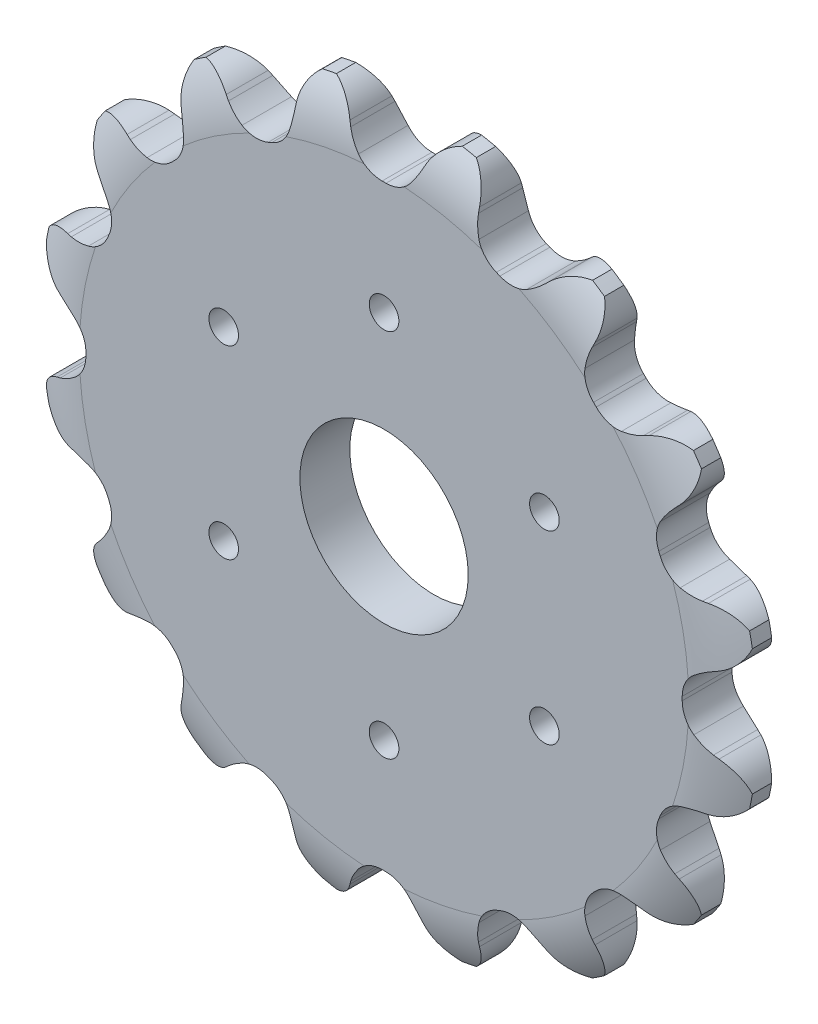
SolidWorks part; units mm, degrees
material "AISI 304"
ref_plane "Спереди" through (0, 0, 0) normal (0, 0, 1) x (1, 0, 0)
ref_plane "Сверху" through (0, 0, 0) normal (0, 1, 0) x (1, 0, 0)
ref_plane "Справа" through (0, 0, 0) normal (1, 0, 0) x (0, 0, -1)
other "Configuration Table"
sketch "Эскиз1" plane through (0, 0, 0) normal (0, 0, 1) x (1, 0, 0)
  line L0 (0, 0) -> (0, 106.534) construction
  line L1 (-0.572, 88.5752) -> (-0.572, 97.6453) construction
  line L2 (0, 0) -> (-23.7583, 119.4411) construction
  line L3 (-0.572, 97.6453) -> (-7.6457, 91.9681) construction
  line L4 (-0.572, 97.6453) -> (10.627, 106.6335) construction
  line L5 (-10.7356, 97.0103) -> (10.627, 106.6335) construction
  line L6 (-10.7356, 97.0103) -> (-11.3155, 98.2977)
  line L7 (-11.3155, 98.2977) -> (-22.4025, 93.3034) construction
  line L8 (10.7356, 97.0103) -> (11.3155, 98.2977)
  line L9 (27.2059, 93.7342) -> (27.1627, 95.1455)
  line L10 (47.0426, 85.5175) -> (48.0711, 86.485)
  line L11 (61.0055, 76.1879) -> (61.5057, 77.5083)
  line L12 (76.1879, 61.0055) -> (77.5083, 61.5057)
  line L13 (85.5175, 47.0426) -> (86.485, 48.0711)
  line L14 (93.7342, 27.2059) -> (95.1455, 27.1627)
  line L15 (97.0103, 10.7356) -> (98.2977, 11.3155)
  line L16 (97.0103, -10.7356) -> (98.2977, -11.3155)
  line L17 (93.7342, -27.2059) -> (95.1455, -27.1627)
  line L18 (85.5175, -47.0426) -> (86.485, -48.0711)
  line L19 (76.1879, -61.0055) -> (77.5083, -61.5057)
  line L20 (61.0055, -76.1879) -> (61.5057, -77.5083)
  line L21 (47.0426, -85.5175) -> (48.0711, -86.485)
  line L22 (27.2059, -93.7342) -> (27.1627, -95.1455)
  line L23 (10.7356, -97.0103) -> (11.3155, -98.2977)
  line L24 (-10.7356, -97.0103) -> (-11.3155, -98.2977)
  line L25 (-27.2059, -93.7342) -> (-27.1627, -95.1455)
  line L26 (-47.0426, -85.5175) -> (-48.0711, -86.485)
  line L27 (-61.0055, -76.1879) -> (-61.5057, -77.5083)
  line L28 (-76.1879, -61.0055) -> (-77.5083, -61.5057)
  line L29 (-85.5175, -47.0426) -> (-86.485, -48.0711)
  line L30 (-93.7342, -27.2059) -> (-95.1455, -27.1627)
  line L31 (-97.0103, -10.7356) -> (-98.2977, -11.3155)
  line L32 (-97.0103, 10.7356) -> (-98.2977, 11.3155)
  line L33 (-93.7342, 27.2059) -> (-95.1455, 27.1627)
  line L34 (-85.5175, 47.0426) -> (-86.485, 48.0711)
  line L35 (-76.1879, 61.0055) -> (-77.5083, 61.5057)
  line L36 (-61.0055, 76.1879) -> (-61.5057, 77.5083)
  line L37 (-47.0426, 85.5175) -> (-48.0711, 86.485)
  line L38 (-27.2059, 93.7342) -> (-27.1627, 95.1455)
  arc A0 (-18.6878, 104.8821) -> (-22.8713, 104.05) centre (0, 0) ccw
  circle A1 centre (0, 0) radius 97.647 construction
  arc A2 (0.572, 88.5752) -> (-0.572, 88.5752) centre (0, 0) ccw
  arc A3 (-0.572, 88.5752) -> (-7.6457, 91.9681) centre (-0.572, 97.6453) cw
  arc A4 (-7.6457, 91.9681) -> (-10.7356, 97.0103) centre (10.627, 106.6335) cw
  arc A5 (-11.3155, 98.2977) -> (-18.6878, 104.8821) centre (-22.4025, 93.3034) ccw
  arc A6 (0.572, 88.5752) -> (7.6457, 91.9681) centre (0.572, 97.6453) ccw
  arc A7 (7.6457, 91.9681) -> (10.7356, 97.0103) centre (-10.627, 106.6335) ccw
  arc A8 (11.3155, 98.2977) -> (18.6878, 104.8821) centre (22.4025, 93.3034) cw
  arc A9 (27.1627, 95.1455) -> (22.8713, 104.05) centre (15.0084, 94.7742) ccw
  arc A10 (28.131, 87.8933) -> (27.2059, 93.7342) centre (50.6249, 94.4497) cw
  arc A11 (33.3678, 82.0517) -> (28.131, 87.8933) centre (36.8388, 90.4314) cw
  arc A12 (34.4247, 81.6139) -> (33.3678, 82.0517) centre (0, 0) ccw
  arc A13 (34.4247, 81.6139) -> (42.2584, 82.0416) centre (37.8957, 89.9936) ccw
  arc A14 (42.2584, 82.0416) -> (47.0426, 85.5175) centre (30.9888, 102.5833) ccw
  arc A15 (48.0711, 86.485) -> (57.402, 89.7469) centre (56.4029, 77.628) cw
  arc A16 (61.5057, 77.5083) -> (60.9486, 87.3771) centre (50.1345, 81.8165) ccw
  arc A17 (59.6249, 70.4376) -> (61.0055, 76.1879) centre (82.9157, 67.8868) cw
  arc A18 (62.2276, 63.0366) -> (59.6249, 70.4376) centre (68.6412, 69.4501) cw
  arc A19 (63.0366, 62.2276) -> (62.2276, 63.0366) centre (0, 0) ccw
  arc A20 (63.0366, 62.2276) -> (70.4376, 59.6249) centre (69.4501, 68.6412) ccw
  arc A21 (70.4376, 59.6249) -> (76.1879, 61.0055) centre (67.8868, 82.9157) ccw
  arc A22 (77.5083, 61.5057) -> (87.3771, 60.9486) centre (81.8165, 50.1345) cw
  arc A23 (86.485, 48.0711) -> (89.7469, 57.402) centre (77.628, 56.4029) ccw
  arc A24 (82.0416, 42.2584) -> (85.5175, 47.0426) centre (102.5833, 30.9888) cw
  arc A25 (81.6139, 34.4247) -> (82.0416, 42.2584) centre (89.9936, 37.8957) cw
  arc A26 (82.0517, 33.3678) -> (81.6139, 34.4247) centre (0, 0) ccw
  arc A27 (82.0517, 33.3678) -> (87.8933, 28.131) centre (90.4314, 36.8388) ccw
  arc A28 (87.8933, 28.131) -> (93.7342, 27.2059) centre (94.4497, 50.6249) ccw
  arc A29 (95.1455, 27.1627) -> (104.05, 22.8713) centre (94.7742, 15.0084) cw
  arc A30 (98.2977, 11.3155) -> (104.8821, 18.6878) centre (93.3034, 22.4025) ccw
  arc A31 (91.9681, 7.6457) -> (97.0103, 10.7356) centre (106.6335, -10.627) cw
  arc A32 (88.5752, 0.572) -> (91.9681, 7.6457) centre (97.6453, 0.572) cw
  arc A33 (88.5752, -0.572) -> (88.5752, 0.572) centre (0, 0) ccw
  arc A34 (88.5752, -0.572) -> (91.9681, -7.6457) centre (97.6453, -0.572) ccw
  arc A35 (91.9681, -7.6457) -> (97.0103, -10.7356) centre (106.6335, 10.627) ccw
  arc A36 (98.2977, -11.3155) -> (104.8821, -18.6878) centre (93.3034, -22.4025) cw
  arc A37 (95.1455, -27.1627) -> (104.05, -22.8713) centre (94.7742, -15.0084) ccw
  arc A38 (87.8933, -28.131) -> (93.7342, -27.2059) centre (94.4497, -50.6249) cw
  arc A39 (82.0517, -33.3678) -> (87.8933, -28.131) centre (90.4314, -36.8388) cw
  arc A40 (81.6139, -34.4247) -> (82.0517, -33.3678) centre (0, 0) ccw
  arc A41 (81.6139, -34.4247) -> (82.0416, -42.2584) centre (89.9936, -37.8957) ccw
  arc A42 (82.0416, -42.2584) -> (85.5175, -47.0426) centre (102.5833, -30.9888) ccw
  arc A43 (86.485, -48.0711) -> (89.7469, -57.402) centre (77.628, -56.4029) cw
  arc A44 (77.5083, -61.5057) -> (87.3771, -60.9486) centre (81.8165, -50.1345) ccw
  arc A45 (70.4376, -59.6249) -> (76.1879, -61.0055) centre (67.8868, -82.9157) cw
  arc A46 (63.0366, -62.2276) -> (70.4376, -59.6249) centre (69.4501, -68.6412) cw
  arc A47 (62.2276, -63.0366) -> (63.0366, -62.2276) centre (0, 0) ccw
  arc A48 (62.2276, -63.0366) -> (59.6249, -70.4376) centre (68.6412, -69.4501) ccw
  arc A49 (59.6249, -70.4376) -> (61.0055, -76.1879) centre (82.9157, -67.8868) ccw
  arc A50 (61.5057, -77.5083) -> (60.9486, -87.3771) centre (50.1345, -81.8165) cw
  arc A51 (48.0711, -86.485) -> (57.402, -89.7469) centre (56.4029, -77.628) ccw
  arc A52 (42.2584, -82.0416) -> (47.0426, -85.5175) centre (30.9888, -102.5833) cw
  arc A53 (34.4247, -81.6139) -> (42.2584, -82.0416) centre (37.8957, -89.9936) cw
  arc A54 (33.3678, -82.0517) -> (34.4247, -81.6139) centre (0, 0) ccw
  arc A55 (33.3678, -82.0517) -> (28.131, -87.8933) centre (36.8388, -90.4314) ccw
  arc A56 (28.131, -87.8933) -> (27.2059, -93.7342) centre (50.6249, -94.4497) ccw
  arc A57 (27.1627, -95.1455) -> (22.8713, -104.05) centre (15.0084, -94.7742) cw
  arc A58 (11.3155, -98.2977) -> (18.6878, -104.8821) centre (22.4025, -93.3034) ccw
  arc A59 (7.6457, -91.9681) -> (10.7356, -97.0103) centre (-10.627, -106.6335) cw
  arc A60 (0.572, -88.5752) -> (7.6457, -91.9681) centre (0.572, -97.6453) cw
  arc A61 (-0.572, -88.5752) -> (0.572, -88.5752) centre (0, 0) ccw
  arc A62 (-0.572, -88.5752) -> (-7.6457, -91.9681) centre (-0.572, -97.6453) ccw
  arc A63 (-7.6457, -91.9681) -> (-10.7356, -97.0103) centre (10.627, -106.6335) ccw
  arc A64 (-11.3155, -98.2977) -> (-18.6878, -104.8821) centre (-22.4025, -93.3034) cw
  arc A65 (-27.1627, -95.1455) -> (-22.8713, -104.05) centre (-15.0084, -94.7742) ccw
  arc A66 (-28.131, -87.8933) -> (-27.2059, -93.7342) centre (-50.6249, -94.4497) cw
  arc A67 (-33.3678, -82.0517) -> (-28.131, -87.8933) centre (-36.8388, -90.4314) cw
  arc A68 (-34.4247, -81.6139) -> (-33.3678, -82.0517) centre (0, 0) ccw
  arc A69 (-34.4247, -81.6139) -> (-42.2584, -82.0416) centre (-37.8957, -89.9936) ccw
  arc A70 (-42.2584, -82.0416) -> (-47.0426, -85.5175) centre (-30.9888, -102.5833) ccw
  arc A71 (-48.0711, -86.485) -> (-57.402, -89.7469) centre (-56.4029, -77.628) cw
  arc A72 (-61.5057, -77.5083) -> (-60.9486, -87.3771) centre (-50.1345, -81.8165) ccw
  arc A73 (-59.6249, -70.4376) -> (-61.0055, -76.1879) centre (-82.9157, -67.8868) cw
  arc A74 (-62.2276, -63.0366) -> (-59.6249, -70.4376) centre (-68.6412, -69.4501) cw
  arc A75 (-63.0366, -62.2276) -> (-62.2276, -63.0366) centre (0, 0) ccw
  arc A76 (-63.0366, -62.2276) -> (-70.4376, -59.6249) centre (-69.4501, -68.6412) ccw
  arc A77 (-70.4376, -59.6249) -> (-76.1879, -61.0055) centre (-67.8868, -82.9157) ccw
  arc A78 (-77.5083, -61.5057) -> (-87.3771, -60.9486) centre (-81.8165, -50.1345) cw
  arc A79 (-86.485, -48.0711) -> (-89.7469, -57.402) centre (-77.628, -56.4029) ccw
  arc A80 (-82.0416, -42.2584) -> (-85.5175, -47.0426) centre (-102.5833, -30.9888) cw
  arc A81 (-81.6139, -34.4247) -> (-82.0416, -42.2584) centre (-89.9936, -37.8957) cw
  arc A82 (-82.0517, -33.3678) -> (-81.6139, -34.4247) centre (0, 0) ccw
  arc A83 (-82.0517, -33.3678) -> (-87.8933, -28.131) centre (-90.4314, -36.8388) ccw
  arc A84 (-87.8933, -28.131) -> (-93.7342, -27.2059) centre (-94.4497, -50.6249) ccw
  arc A85 (-95.1455, -27.1627) -> (-104.05, -22.8713) centre (-94.7742, -15.0084) cw
  arc A86 (-98.2977, -11.3155) -> (-104.8821, -18.6878) centre (-93.3034, -22.4025) ccw
  arc A87 (-91.9681, -7.6457) -> (-97.0103, -10.7356) centre (-106.6335, 10.627) cw
  arc A88 (-88.5752, -0.572) -> (-91.9681, -7.6457) centre (-97.6453, -0.572) cw
  arc A89 (-88.5752, 0.572) -> (-88.5752, -0.572) centre (0, 0) ccw
  arc A90 (-88.5752, 0.572) -> (-91.9681, 7.6457) centre (-97.6453, 0.572) ccw
  arc A91 (-91.9681, 7.6457) -> (-97.0103, 10.7356) centre (-106.6335, -10.627) ccw
  arc A92 (-98.2977, 11.3155) -> (-104.8821, 18.6878) centre (-93.3034, 22.4025) cw
  arc A93 (-95.1455, 27.1627) -> (-104.05, 22.8713) centre (-94.7742, 15.0084) ccw
  arc A94 (-87.8933, 28.131) -> (-93.7342, 27.2059) centre (-94.4497, 50.6249) cw
  arc A95 (-82.0517, 33.3678) -> (-87.8933, 28.131) centre (-90.4314, 36.8388) cw
  arc A96 (-81.6139, 34.4247) -> (-82.0517, 33.3678) centre (0, 0) ccw
  arc A97 (-81.6139, 34.4247) -> (-82.0416, 42.2584) centre (-89.9936, 37.8957) ccw
  arc A98 (-82.0416, 42.2584) -> (-85.5175, 47.0426) centre (-102.5833, 30.9888) ccw
  arc A99 (-86.485, 48.0711) -> (-89.7469, 57.402) centre (-77.628, 56.4029) cw
  arc A100 (-77.5083, 61.5057) -> (-87.3771, 60.9486) centre (-81.8165, 50.1345) ccw
  arc A101 (-70.4376, 59.6249) -> (-76.1879, 61.0055) centre (-67.8868, 82.9157) cw
  arc A102 (-63.0366, 62.2276) -> (-70.4376, 59.6249) centre (-69.4501, 68.6412) cw
  arc A103 (-62.2276, 63.0366) -> (-63.0366, 62.2276) centre (0, 0) ccw
  arc A104 (-62.2276, 63.0366) -> (-59.6249, 70.4376) centre (-68.6412, 69.4501) ccw
  arc A105 (-59.6249, 70.4376) -> (-61.0055, 76.1879) centre (-82.9157, 67.8868) ccw
  arc A106 (-61.5057, 77.5083) -> (-60.9486, 87.3771) centre (-50.1345, 81.8165) cw
  arc A107 (-48.0711, 86.485) -> (-57.402, 89.7469) centre (-56.4029, 77.628) ccw
  arc A108 (-42.2584, 82.0416) -> (-47.0426, 85.5175) centre (-30.9888, 102.5833) cw
  arc A109 (-34.4247, 81.6139) -> (-42.2584, 82.0416) centre (-37.8957, 89.9936) cw
  arc A110 (-33.3678, 82.0517) -> (-34.4247, 81.6139) centre (0, 0) ccw
  arc A111 (-33.3678, 82.0517) -> (-28.131, 87.8933) centre (-36.8388, 90.4314) ccw
  arc A112 (-28.131, 87.8933) -> (-27.2059, 93.7342) centre (-50.6249, 94.4497) ccw
  arc A113 (-27.1627, 95.1455) -> (-22.8713, 104.05) centre (-15.0084, 94.7742) cw
  arc A114 (22.8713, 104.05) -> (18.6878, 104.8821) centre (0, 0) ccw
  arc A115 (60.9486, 87.3771) -> (57.402, 89.7469) centre (0, 0) ccw
  arc A116 (-57.402, 89.7469) -> (-60.9486, 87.3771) centre (0, 0) ccw
  arc A117 (-87.3771, 60.9486) -> (-89.7469, 57.402) centre (0, 0) ccw
  arc A118 (-104.05, 22.8713) -> (-104.8821, 18.6878) centre (0, 0) ccw
  arc A119 (-104.8821, -18.6878) -> (-104.05, -22.8713) centre (0, 0) ccw
  arc A120 (-89.7469, -57.402) -> (-87.3771, -60.9486) centre (0, 0) ccw
  arc A121 (-60.9486, -87.3771) -> (-57.402, -89.7469) centre (0, 0) ccw
  arc A122 (-22.8713, -104.05) -> (-18.6878, -104.8821) centre (0, 0) ccw
  arc A123 (18.6878, -104.8821) -> (22.8713, -104.05) centre (0, 0) ccw
  arc A124 (57.402, -89.7469) -> (60.9486, -87.3771) centre (0, 0) ccw
  arc A125 (87.3771, -60.9486) -> (89.7469, -57.402) centre (0, 0) ccw
  arc A126 (104.05, -22.8713) -> (104.8821, -18.6878) centre (0, 0) ccw
  arc A127 (104.8821, 18.6878) -> (104.05, 22.8713) centre (0, 0) ccw
  arc A128 (89.7469, 57.402) -> (87.3771, 60.9486) centre (0, 0) ccw
  point P265 (0, 0)
  dimension "D1" = 213.068
  dimension "D2" = 195.294
  dimension "D3" = 177.154
  dimension "D4" = 0.572
  dimension "D5" = 11.25
  dimension "D6" = 51.25
  dimension "D7" = 23.43
  dimension "D8" = 14.5
  dimension "D9" = 1.412
  dimension "D10" = 12.16
  dimension "D11" = 16
extrude "Бобышка-Вытянуть1" add sketch "Эскиз1" along normal mid plane 14.823
sketch "Эскиз4" plane through (0, 0, 0) normal (1, 0, 0) x (0, 0, -1)
  line L0 (23.1035, 90.5221) -> (86.5749, 90.5221) construction
  line L1 (-7.4115, 104.8821) -> (7.4115, 104.8821) construction
  line L2 (-7.4115, 104.8821) -> (-7.4115, 80.5418) construction
  line L3 (-7.4115, 87.3771) -> (-7.4115, 77.5083) construction
  line L4 (0, 0) -> (0, 128.247) construction
  line L5 (0, 50) -> (0, -50) construction
  line L6 (7.4115, 104.8821) -> (7.4115, 80.5418) construction
  line L7 (-7.4115, 90.5221) -> (-15.5204, 90.5221)
  line L8 (-15.5204, 90.5221) -> (-15.5204, 116.7797)
  line L9 (-15.5204, 116.7797) -> (14.2207, 116.7797)
  line L10 (14.2207, 116.7797) -> (14.2207, 90.5221)
  line L11 (14.2207, 90.5221) -> (7.4115, 90.5221)
  line L12 (0, 0) -> (24.8056, 0) construction
  line L13 (50, 0) -> (-50, 0) construction
  arc A0 (0, 110.4568) -> (-7.4115, 90.5221) centre (23.1035, 90.5221) ccw
  arc A1 (0, 110.4568) -> (7.4115, 90.5221) centre (-23.1035, 90.5221) cw
  dimension "D2" = 61.03
  dimension "D1" = 14.36
revolve "Вырез-Повернуть1" cut sketch "Эскиз4" angle 360 about L12
sketch "Эскиз5" plane through (0, 0, 7.4115) normal (0, 0, 1) x (1, 0, 0)
  line L0 (0, 55) -> (0, 0) construction
  circle A0 centre (0, 0) radius 25
  circle A1 centre (0, 0) radius 55 construction
  circle A2 centre (0, 55) radius 4.4
  circle A3 centre (47.6314, 27.5) radius 4.4
  circle A4 centre (47.6314, -27.5) radius 4.4
  circle A5 centre (0, -55) radius 4.4
  circle A6 centre (-47.6314, -27.5) radius 4.4
  circle A7 centre (-47.6314, 27.5) radius 4.4
  point P19 (0, 0)
  dimension "D1" = 50
  dimension "D2" = 110
  dimension "D3" = 8.8
  dimension "D4" = 6
extrude "Вырез-Вытянуть1" cut sketch "Эскиз5" against normal through all both and the other way through all
